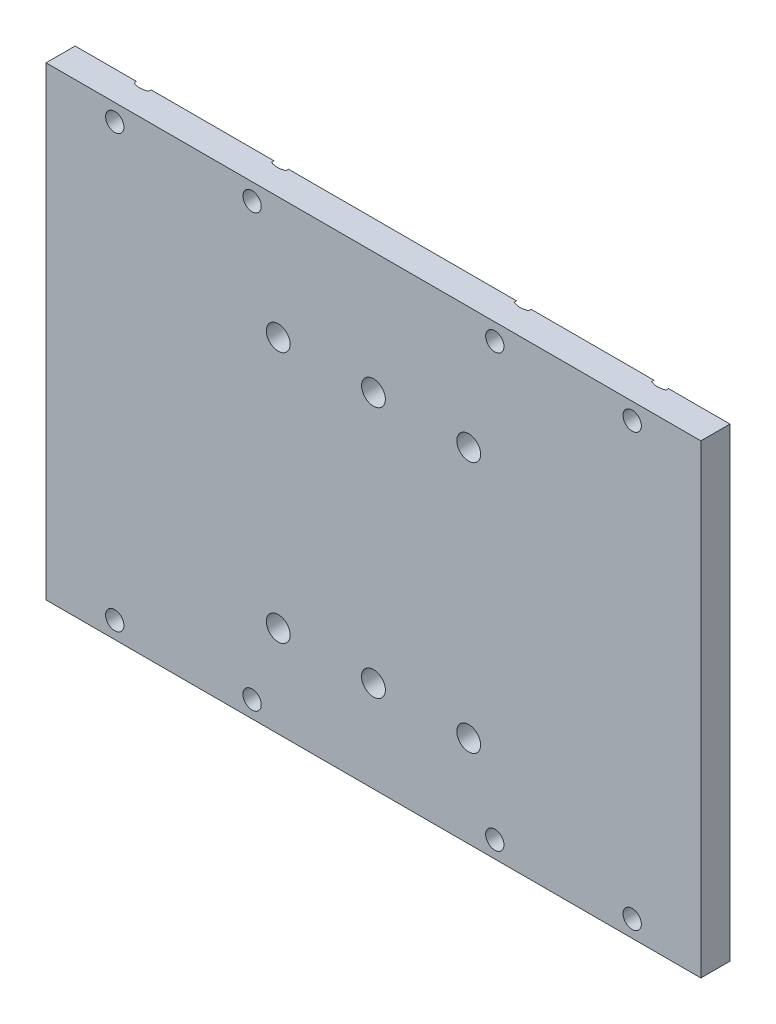
SolidWorks part; units mm, degrees
ref_plane "Plano frontal" through (0, 0, 0) normal (0, 0, 1) x (1, 0, 0)
ref_plane "Plano superior" through (0, 0, 0) normal (0, 1, 0) x (1, 0, 0)
ref_plane "Plano direito" through (0, 0, 0) normal (1, 0, 0) x (0, 0, -1)
sketch "Esboço1" plane through (0, 0, 0) normal (0, 0, 1) x (1, 0, 0)
  line L0 (71.505, 50.8) -> (-71.505, -50.8) construction
  line L1 (-71.505, 50.8) -> (71.505, 50.8)
  line L2 (-71.505, 50.8) -> (-71.505, -50.8)
  line L3 (-71.505, -50.8) -> (71.505, -50.8)
  line L4 (71.505, 50.8) -> (71.505, -50.8)
  dimension "D1" = 143.01
  dimension "D2" = 101.6
extrude "Ressalto-extrusão1" add sketch "Esboço1" along normal blind 6.35
sketch "Esboço2" plane through (0, 0, 0) normal (0, 0, -1) x (-1, 0, 0)
  line L1 (-71.505, -50.8) -> (-71.505, 50.8) construction
  line L2 (-71.505, 50.8) -> (71.505, 50.8) construction
  line L3 (0, 50.8) -> (0, -50.8) construction
  line L4 (71.505, -50.8) -> (-71.505, -50.8) construction
  line L6 (36.2584, 0) -> (-28.1024, 0) construction
  circle A0 centre (56.505, 47.125) radius 2
  circle A1 centre (26.505, 47.125) radius 2
  circle A2 centre (26.505, -47.125) radius 2
  circle A3 centre (56.505, -47.125) radius 2
  circle A4 centre (-26.505, 47.125) radius 2
  circle A5 centre (-56.505, 47.125) radius 2
  circle A6 centre (-56.505, -47.125) radius 2
  circle A7 centre (-26.505, -47.125) radius 2
  dimension "D6" = 4
  dimension "D7" = 4
  dimension "D1" = 3.675
  dimension "D3" = 15
  dimension "D4" = 45
  dimension "D5" = 3.675
extrude "Corte-extrusão1" cut sketch "Esboço2" against normal blind 13
sketch "Esboço3" plane through (0, 0, 6.35) normal (0, 0, 1) x (1, 0, 0)
  line L1 (71.505, -50.8) -> (71.505, 50.8) construction
  line L2 (-71.505, -50.8) -> (71.505, -50.8) construction
  line L3 (20.8, -30.8) -> (-20.8, -30.8) construction
  line L4 (-20.8, -30.8) -> (-20.8, 24.2) construction
  line L5 (-20.8, 24.2) -> (20.8, 24.2) construction
  line L6 (20.8, 24.2) -> (20.8, -30.8) construction
  line L7 (20.8, -3.3) -> (-20.8, -3.3) construction
  line L8 (-71.505, 50.8) -> (-71.505, -50.8) construction
  line L9 (0, -30.8) -> (0, 24.2) construction
  circle A0 centre (20.8, -30.8) radius 2.6
  circle A1 centre (0, -30.8) radius 2.6
  circle A2 centre (-20.8, -30.8) radius 2.6
  circle A3 centre (-20.8, 24.2) radius 2.6
  circle A4 centre (0, 24.2) radius 2.6
  circle A5 centre (20.8, 24.2) radius 2.6
  dimension "D1" = 50.705
  dimension "D2" = 20
  dimension "D3" = 50.705
  dimension "D4" = 55
  dimension "D5" = 5.2
  dimension "D6" = 5.2
extrude "Corte-extrusão2" cut sketch "Esboço3" against normal blind 7
sketch "Esboço4" plane through (0, 0, 0) normal (0, 0, -1) x (-1, 0, 0)
  line L0 (0, 23.8159) -> (0, -18.1553) construction
  line L1 (26.4232, 0) -> (-27.8086, 0) construction
  line L2 (-71.505, 50.8) -> (71.505, 50.8) construction
  circle A0 centre (-26.505, 47.125) radius 4
  circle A1 centre (-56.505, 47.125) radius 4
  circle A2 centre (-56.505, -47.125) radius 4
  circle A3 centre (-26.505, -47.125) radius 4
  circle A4 centre (26.505, -47.125) radius 4
  circle A5 centre (56.505, 47.125) radius 4
  circle A6 centre (26.505, 47.125) radius 4
  circle A7 centre (56.505, -47.125) radius 4
  dimension "D1" = 15
  dimension "D2" = 45
  dimension "D3" = 3.675
  dimension "D4" = 3.675
  dimension "D5" = 8
  dimension "D6" = 8
extrude "Corte-extrusão3" cut sketch "Esboço4" against normal blind 0.55
sketch "Croquis1" plane through (0, 0, 0.55) normal (0, 0, -1) x (-1, 0, 0)
  line L0 (0, 12.3789) -> (0, -11.3102) construction
  line L1 (17.8114, 0) -> (-18.702, 0) construction
  line L2 (-24.9256, 50.8) -> (24.9256, 50.8) construction
  line L3 (58.0844, 50.8) -> (71.505, 50.8) construction
  line L4 (71.505, 50.8) -> (71.505, -50.8) construction
  circle A0 centre (56.505, 47.125) radius 4
  circle A1 centre (26.505, 47.125) radius 4
  circle A2 centre (-26.505, 47.125) radius 4
  circle A3 centre (-56.505, 47.125) radius 4
  circle A4 centre (-56.505, -47.125) radius 4
  circle A5 centre (-26.505, -47.125) radius 4
  circle A6 centre (26.505, -47.125) radius 4
  circle A7 centre (56.505, -47.125) radius 4
  dimension "D5" = 8
  dimension "D6" = 8
  dimension "D1" = 3.675
  dimension "D2" = 3.675
  dimension "D3" = 15
  dimension "D4" = 45
extrude "Cortar-Extruir1" cut sketch "Croquis1" against normal blind 2 draft 45
